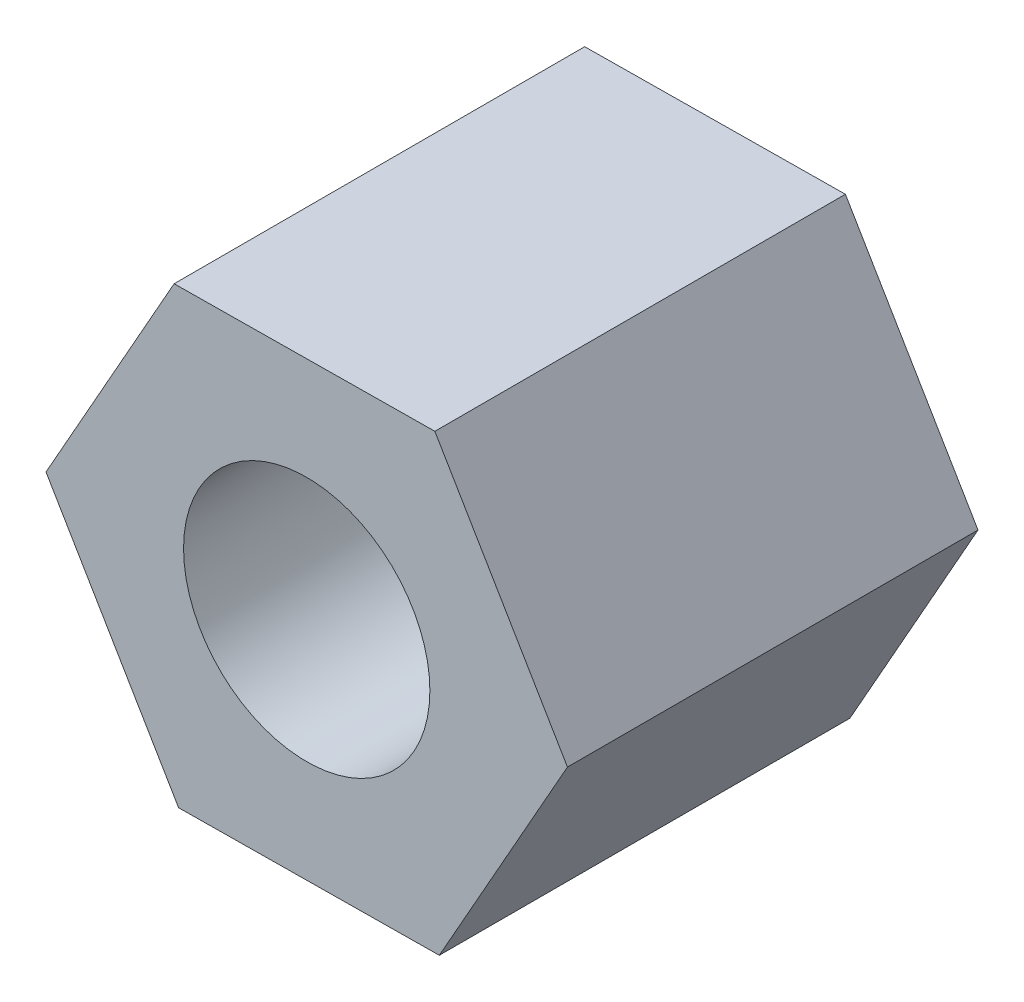
SolidWorks part; units mm, degrees
material "硅橡胶"
ref_plane "前视基准面" through (0, 0, 0) normal (0, 0, 1) x (1, 0, 0)
ref_plane "上视基准面" through (0, 0, 0) normal (0, 1, 0) x (1, 0, 0)
ref_plane "右视基准面" through (0, 0, 0) normal (1, 0, 0) x (0, 0, -1)
sketch "草图1" plane through (0, 0, 0) normal (0, 0, 1) x (1, 0, 0)
  line L1 (1.6148, -2.7342) -> (3.1753, 0.0314)
  line L2 (3.1753, 0.0314) -> (1.5605, 2.7656)
  line L3 (1.5605, 2.7656) -> (-1.6148, 2.7342)
  line L4 (-1.6148, 2.7342) -> (-3.1753, -0.0314)
  line L5 (-3.1753, -0.0314) -> (-1.5605, -2.7656)
  line L6 (-1.5605, -2.7656) -> (1.6148, -2.7342)
  circle A0 centre (0, 0) radius 2.75 construction
  circle A1 centre (0, 0) radius 1.5
  dimension "D2" = 3
  dimension "D1" = 5.5
extrude "凸台-拉伸1" add sketch "草图1" along normal blind 5
